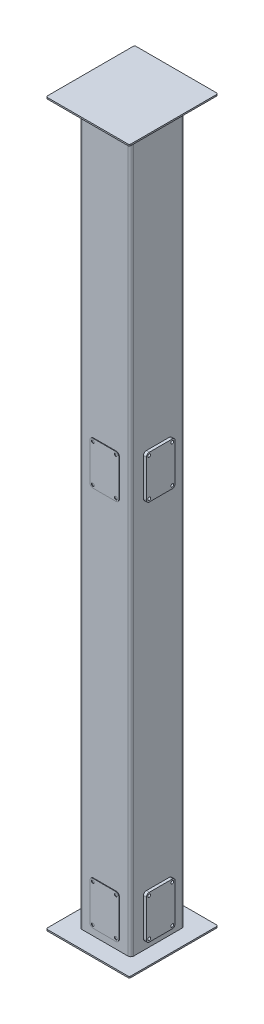
SolidWorks part; units mm, degrees
ref_plane "前视基准面" through (0, 0, 0) normal (0, 0, 1) x (1, 0, 0)
ref_plane "上视基准面" through (0, 0, 0) normal (0, 1, 0) x (1, 0, 0)
ref_plane "右视基准面" through (0, 0, 0) normal (1, 0, 0) x (0, 0, -1)
sketch "草图1" plane through (0, 0, 0) normal (0, 1, 0) x (1, 0, 0)
  line L1 (-280, 300) -> (280, 300)
  line L2 (-290, 290) -> (-290, -270)
  line L3 (-280, -280) -> (280, -280)
  line L4 (290, 290) -> (290, -270)
  arc A0 (-280, 300) -> (-290, 290) centre (-280, 290) ccw
  arc A1 (-290, -270) -> (-280, -280) centre (-280, -270) ccw
  arc A2 (280, -280) -> (290, -270) centre (280, -270) ccw
  arc A3 (290, 290) -> (280, 300) centre (280, 290) ccw
  dimension "D1" = 10
  dimension "D2" = 290
extrude "凸台-拉伸1" add sketch "草图1" along normal blind 10
sketch "草图2" plane through (0, 10, 0) normal (0, 1, 0) x (1, 0, 0)
  line L0 (0, -55) -> (0, 55) construction
  line L1 (-240, 240) -> (240, 240)
  line L2 (-240, 240) -> (-240, -240)
  line L3 (-240, -240) -> (240, -240)
  line L4 (240, 240) -> (240, -240)
  circle A0 centre (-240, 240) radius 16
  circle A1 centre (240, 240) radius 16
  circle A2 centre (-240, -240) radius 16
  circle A3 centre (240, -240) radius 16
  dimension "D1" = 240
  dimension "D2" = 240
sketch "草图3" plane through (0, 0, 0) normal (0, 1, 0) x (1, 0, 0)
  line L0 (0, -5.5) -> (0, 5.5) construction
  line L5 (-160, 170) -> (160, 170)
  line L6 (-170, 160) -> (-170, -160)
  line L7 (-160, -170) -> (160, -170)
  line L8 (170, 160) -> (170, -160)
  arc A4 (-170, -160) -> (-160, -170) centre (-160, -160) ccw
  arc A5 (160, -170) -> (170, -160) centre (160, -160) ccw
  arc A6 (170, 160) -> (160, 170) centre (160, 160) ccw
  arc A7 (-170, 160) -> (-160, 170) centre (-160, 160) cw
  dimension "D1" = 10
  dimension "D2" = 170
  dimension "D3" = 170
extrude "拉伸-薄壁1" add sketch "草图3" along normal blind 2510 thin thin type one direction wall 10
mirror "镜向1" about plane through (-160, 2510, 160) normal (0, 1, 0) of bodies 108
scale "缩放比例1" scale about centroid uniform scaling yes scale factor 0.1
sketch "草图4" plane through (0, 0, 17.1975) normal (0, 0, 1) x (1, 0, 0)
  line L9 (10, 2293) -> (10, 2267)
  line L10 (8, 2295) -> (-8, 2295)
  line L16 (-10, 2558) -> (-10, 2532)
  line L17 (8, 2560) -> (-8, 2560)
  line L18 (10, 2558) -> (10, 2532)
  line L19 (8, 2530) -> (-8, 2530)
  line L20 (-28, 2760) -> (28, 2760) construction
  line L21 (-10, 2293) -> (-10, 2267)
  line L22 (8, 2265) -> (-8, 2265)
  line L23 (16, 2260) -> (-16, 2260) construction
  arc A16 (-8, 2530) -> (-10, 2532) centre (-8, 2532) cw
  arc A17 (10, 2558) -> (8, 2560) centre (8, 2558) ccw
  circle A18 centre (8, 2558) radius 1
  circle A19 centre (8, 2532) radius 1
  circle A20 centre (-8, 2558) radius 1
  arc A21 (10, 2532) -> (8, 2530) centre (8, 2532) cw
  arc A22 (-10, 2558) -> (-8, 2560) centre (-8, 2558) cw
  circle A23 centre (-8, 2532) radius 1
  arc A24 (-8, 2265) -> (-10, 2267) centre (-8, 2267) cw
  circle A25 centre (-8, 2267) radius 1
  arc A26 (-10, 2293) -> (-8, 2295) centre (-8, 2293) cw
  arc A27 (10, 2267) -> (8, 2265) centre (8, 2267) cw
  circle A28 centre (8, 2293) radius 1
  arc A29 (10, 2293) -> (8, 2295) centre (8, 2293) ccw
  circle A30 centre (-8, 2293) radius 1
  circle A31 centre (8, 2267) radius 1
  dimension "D7" = 200
  dimension "D1" = 5
extrude "凸台-拉伸2" add sketch "草图4" along normal blind 2
mirror "镜向2" about plane through (0, 0, 0) normal (0, 0, 1) of bodies 124 114
sketch "草图6" plane through (18, 0, 0) normal (1, 0, 0) x (0, 0, -1)
  line L12 (-8, 2530) -> (8, 2530)
  line L13 (-8, 2560) -> (8, 2560)
  line L14 (-10, 2558) -> (-10, 2532)
  line L15 (10, 2558) -> (10, 2532)
  line L16 (-8, 2295) -> (8, 2295)
  line L17 (-10, 2293) -> (-10, 2267)
  line L18 (10, 2293) -> (10, 2267)
  line L19 (-8, 2265) -> (8, 2265)
  line L20 (-29.8025, 2260) -> (29.8025, 2260) construction
  arc A16 (10, 2558) -> (8, 2560) centre (8, 2558) ccw
  arc A17 (-10, 2532) -> (-8, 2530) centre (-8, 2532) ccw
  circle A18 centre (-8, 2532) radius 1
  arc A19 (-10, 2558) -> (-8, 2560) centre (-8, 2558) cw
  circle A20 centre (-8, 2558) radius 1
  circle A21 centre (8, 2532) radius 1
  circle A22 centre (8, 2558) radius 1
  arc A23 (8, 2530) -> (10, 2532) centre (8, 2532) ccw
  circle A24 centre (8, 2267) radius 1
  arc A25 (10, 2293) -> (8, 2295) centre (8, 2293) ccw
  circle A26 centre (-8, 2293) radius 1
  circle A28 centre (-8, 2267) radius 1
  arc A32 (-10, 2293) -> (-8, 2295) centre (-8, 2293) cw
  arc A33 (8, 2265) -> (10, 2267) centre (8, 2267) ccw
  circle A34 centre (8, 2293) radius 1
  arc A35 (-10, 2267) -> (-8, 2265) centre (-8, 2267) ccw
  dimension "D1" = 5
extrude "凸台-拉伸3" add sketch "草图6" along normal blind 2
mirror "镜向3" about plane through (0, 0, 0) normal (1, 0, 0) of "凸台-拉伸3"
